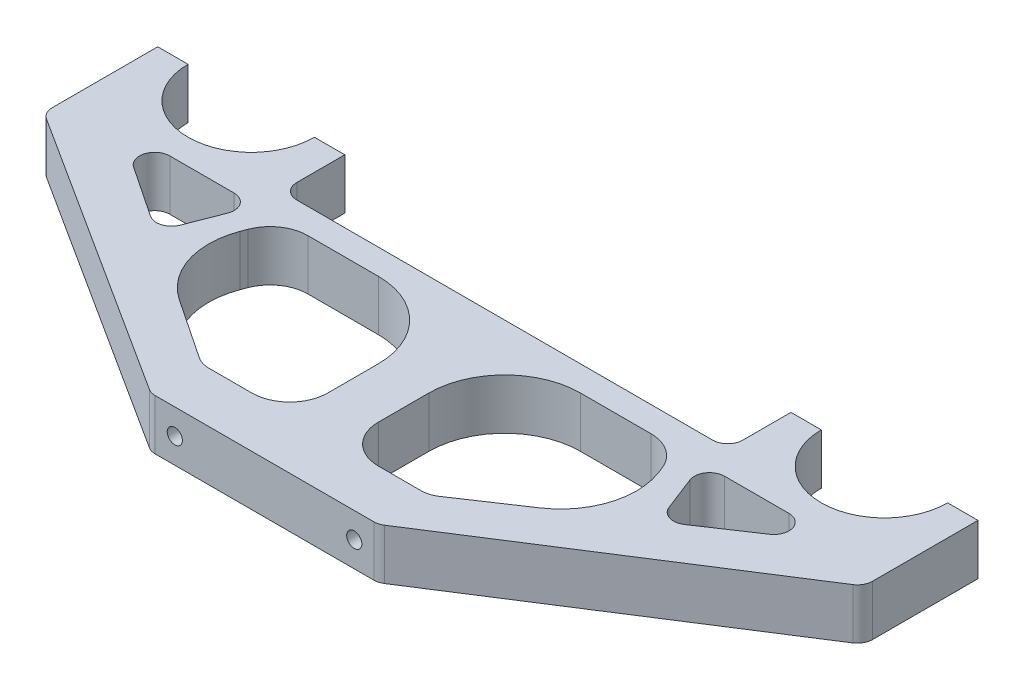
SolidWorks part; units mm, degrees
ref_plane "Front Plane" through (0, 0, 0) normal (0, 0, 1) x (1, 0, 0)
ref_plane "Top Plane" through (0, 0, 0) normal (0, 1, 0) x (1, 0, 0)
ref_plane "Right Plane" through (0, 0, 0) normal (1, 0, 0) x (0, 0, -1)
sketch "Sketch1" plane through (0, 0, 0) normal (0, 1, 0) x (1, 0, 0)
  line L0 (0, 0) -> (62.625, 0)
  line L1 (75.125, 0) -> (81.125, 0)
  line L2 (62.625, 12.5) -> (62.625, 17.5)
  line L3 (112.5, 0) -> (106.5, 0)
  line L4 (106.5, 0) -> (106.5, 17.5)
  line L5 (106.5, 17.5) -> (62.625, 17.5)
  line L6 (81.125, 0) -> (81.125, 17.5)
  line L7 (81.125, 17.5) -> (62.625, 17.5)
  line L8 (44.125, -17.5) -> (44.125, 17.5)
  line L10 (44.125, 17.5) -> (81.125, 17.5)
  line L11 (81.125, -17.5) -> (81.125, 17.5)
  line L12 (44.125, -17.5) -> (81.125, 17.5) construction
  line L13 (44.125, 17.5) -> (81.125, -17.5) construction
  line L14 (44.125, -17.5) -> (5, -17.5)
  line L15 (5, -17.5) -> (0, -17.5)
  line L16 (0, -17.5) -> (0, -12.5)
  line L17 (0, -12.5) -> (5, -12.5)
  line L18 (5, -12.5) -> (44.125, -12.5)
  line L19 (5, -12.5) -> (5, -17.5)
  line L20 (5, -17.5) -> (5, -55)
  line L21 (0, -55) -> (10, -55)
  line L22 (5, -55) -> (0, -55)
  line L23 (5, -55) -> (5, -17.5)
  line L24 (5, -17.5) -> (0, -17.5)
  line L25 (0, -55) -> (0, -17.5)
  line L26 (10, -55) -> (15, -55)
  line L27 (81.125, -17.5) -> (71.125, -17.5)
  line L28 (71.125, -17.5) -> (15, -55)
  line L29 (15, -55) -> (22.5, -55)
  line L30 (81.125, -17.5) -> (81.125, -22.5)
  line L31 (71.125, -17.5) -> (44.125, -17.5)
  line L32 (22.5, -55) -> (22.5, -60)
  line L33 (22.5, -60) -> (81.125, -22.5)
  line L34 (22.5, -60) -> (0, -60)
  line L35 (0, -60) -> (0, -55)
  line L36 (24.5625, -17.5) -> (48.25, -17.5)
  line L37 (24.5625, -17.5) -> (63.25, -17.5)
  line L38 (38.0567, -39.5946) -> (49.6962, -31.8177)
  line L39 (71.125, -17.5) -> (5, -55)
  line L40 (49.6962, -31.8177) -> (44.125, -17.5)
  line L41 (39.125, -17.5) -> (45.5388, -34.5954)
  line L42 (15, -55) -> (15, -50)
  line L43 (15, -50) -> (22.4833, -50)
  line L44 (15, -50) -> (5, -50)
  circle A0 centre (62.625, 0) radius 12.5
  circle A1 centre (44.125, -17.5) radius 5
  circle A2 centre (49.6962, -31.8177) radius 5
  point P9 (62.625, 17.5)
  point P13 (93.8125, 0)
  dimension "D2" = 25
  dimension "D18" = 10
  dimension "D19" = 10
  dimension "D1" = 62.625
  dimension "D3" = 6
  dimension "D4" = 5
  dimension "D6" = 39.125
  dimension "D7" = 5
  dimension "D8" = 5
  dimension "D9" = 5
  dimension "D10" = 37.5
  dimension "D11" = 10
  dimension "D12" = 5
  dimension "D13" = 7.5
  dimension "D14" = 10
  dimension "D15" = 27
  dimension "D16" = 5
  dimension "D17" = 5
  dimension "D20" = 5
  dimension "D5" = 2
extrude "Boss-Extrude1" add sketch "Sketch1" along normal blind 10 contours A1 L31 L27 L11 L1 A0 L0 L8 | A2 L38 L28 L29 L32 L33 L30 L27 | L28 A2 | L39 L41 L28 L40 | L40 A2 L41 L39 | A2 L40 A1 L41 | L41 A1 L40 L14 | L37 A1 L8 L31 | L8 A1 L14 | A1 L18 L19 L14 L37 | L19 L17 L16 L15 | L35 L34 L32 L29 L26 L21 | L43 L42 L28 | L42 L44 L39 L21 L26 | L39 L44 L23
mirror "Mirror1" about plane through (0, 10, 0) normal (-1, 0, 0) of "Boss-Extrude1"
ref_plane "Plane1" through (0, 0, 0) normal (1, 0, 0) x (0, 0, -1)
sketch "Sketch9" plane through (0, 0, 60) normal (0, 0, 1) x (1, 0, 0)
  line L0 (0, 0) -> (0, 10)
  line L1 (22.5, 0) -> (-22.5, 0) construction
  line L2 (22.5, 10) -> (-22.5, 10) construction
  line L3 (0, 5) -> (-17.75, 5)
  line L4 (-17.75, 5) -> (-35.75, 5)
  circle A0 centre (-17.75, 5) radius 1.5
  circle A1 centre (-35.75, 5) radius 1.5
  dimension "D2" = 3
  dimension "D4" = 3
  dimension "D1" = 17.75
  dimension "D3" = 18
extrude "Cut-Extrude5" cut sketch "Sketch9" against normal up to next contours A0
mirror "Mirror2" about plane through (0, 0, 0) normal (1, 0, 0) of "Cut-Extrude5"
fillet "Fillet10" radius 3 1 edges at (71.125, 5, 17.5)
fillet "Fillet11" radius 3 1 edges at (44.125, 5, 17.5)
fillet "Fillet12" radius 3 1 edges at (49.6962, 5, 31.8177)
fillet "Fillet13" radius 7.5 1 edges at (39.125, 5, 17.5)
fillet "Fillet14" radius 15 1 edges at (45.5388, 5, 34.5954)
fillet "Fillet16" radius 15 1 edges at (5, 5, 17.5)
fillet "Fillet18" radius 15 1 edges at (-5, 5, 17.5)
fillet "Fillet19" radius 7.5 1 edges at (-39.125, 5, 17.5)
fillet "Fillet22" radius 3 1 edges at (44.125, 5, 12.5)
fillet "Fillet23" radius 3 1 edges at (-44.125, 5, 12.5)
fillet "Fillet24" radius 15 1 edges at (-45.5388, 5, 34.5954)
fillet "Fillet25" radius 3 1 edges at (-44.125, 5, 17.5)
fillet "Fillet26" radius 3 1 edges at (-49.6962, 5, 31.8177)
fillet "Fillet27" radius 3 1 edges at (-71.125, 5, 17.5)
fillet "Fillet28" radius 3 1 edges at (22.5, 5, 60)
fillet "Fillet29" radius 3 1 edges at (-22.5, 5, 60)
fillet "Fillet30" radius 3 1 edges at (81.125, 5, 22.5)
fillet "Fillet31" radius 3 1 edges at (-81.125, 5, 22.5)
sketch "Sketch11" plane through (0, 0, 0) normal (0, 0, -1) x (-1, 0, 0)
  line L0 (-78.125, 10) -> (-78.125, 0)
  line L1 (-75.125, 10) -> (-81.125, 10) construction
  line L2 (-75.125, 0) -> (-81.125, 0) construction
  line L3 (-47.125, 10) -> (-47.125, 0)
  line L4 (-44.125, 10) -> (-50.125, 10) construction
  line L5 (-44.125, 0) -> (-50.125, 0) construction
  circle A0 centre (-78.125, 5) radius 1.5
  circle A1 centre (-47.125, 5) radius 1.5
  dimension "D1" = 3
  dimension "D2" = 3
extrude "Cut-Extrude6" cut sketch "Sketch11" against normal blind 7.5 contours A0 | A1
mirror "Mirror3" about plane through (0, 0, 0) normal (1, 0, 0) of "Cut-Extrude6"
fillet "Fillet32" radius 7.5 1 edges at (5, 5, 50)
fillet "Fillet33" radius 5 1 edges at (22.4833, 5, 50)
fillet "Fillet34" radius 7.5 1 edges at (-5, 5, 50)
fillet "Fillet36" radius 5 1 edges at (-22.4833, 5, 50)
